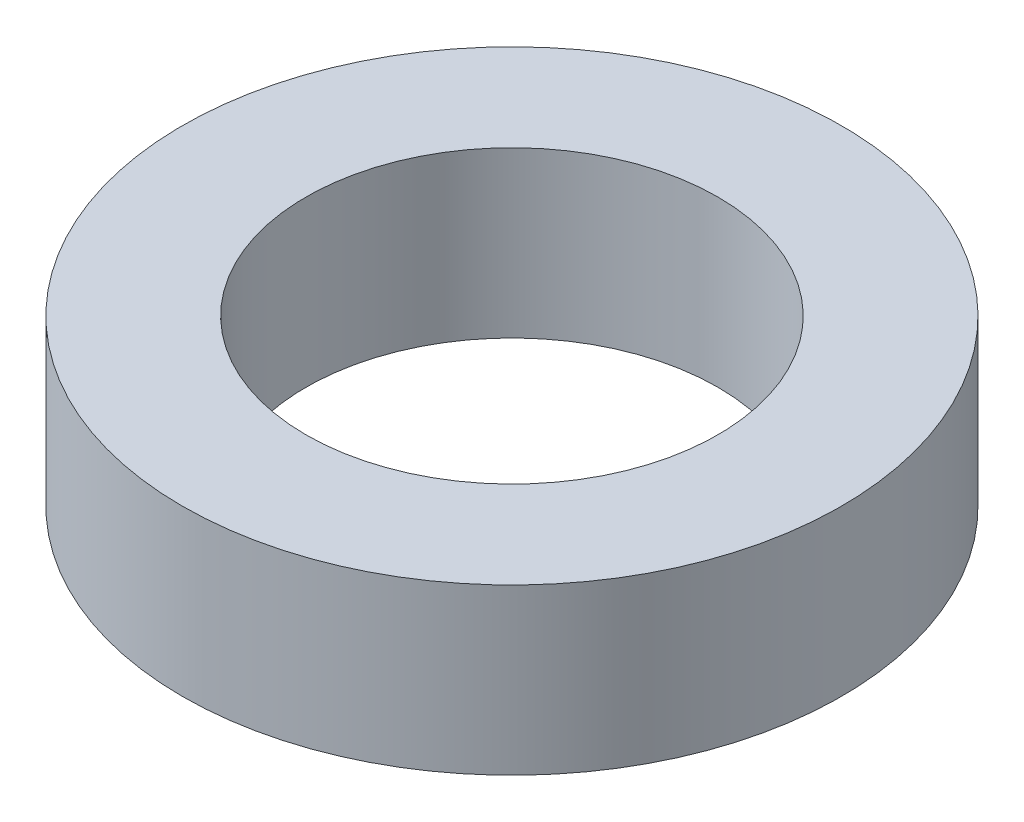
SolidWorks part; units mm, degrees
ref_plane "前视基准面" through (0, 0, 0) normal (0, 0, 1) x (1, 0, 0)
ref_plane "上视基准面" through (0, 0, 0) normal (0, 1, 0) x (1, 0, 0)
ref_plane "右视基准面" through (0, 0, 0) normal (1, 0, 0) x (0, 0, -1)
other "Configuration Table"
sketch "草图1" plane through (0, 0, 0) normal (0, 1, 0) x (1, 0, 0)
  circle A0 centre (0, 0) radius 5
  circle A1 centre (0, 0) radius 8
  dimension "D1" = 10
  dimension "D2" = 16
extrude "凸台-拉伸1" add sketch "草图1" along normal blind 4
